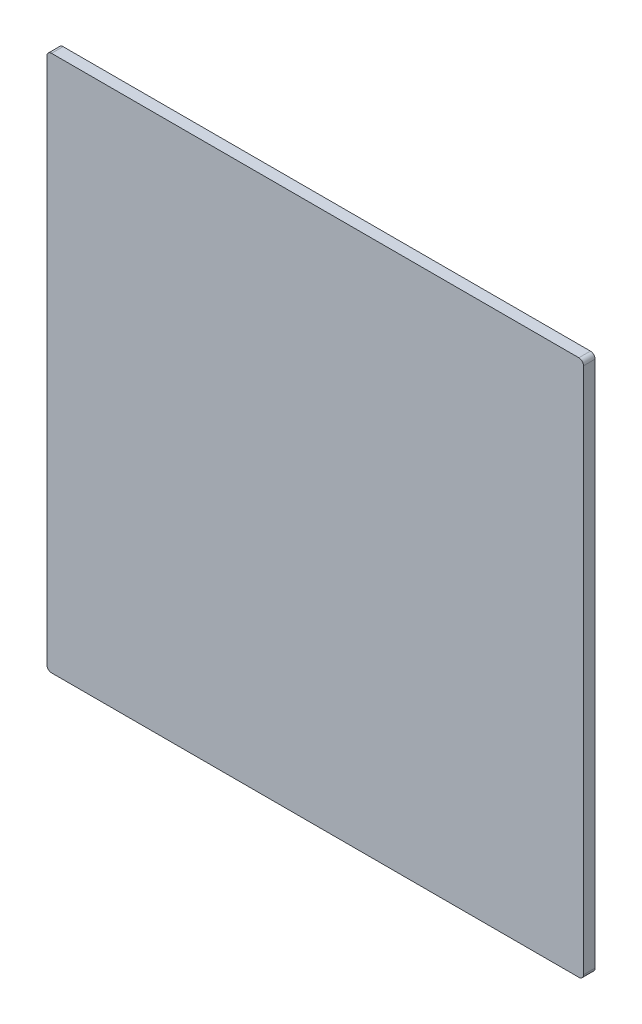
SolidWorks part; units mm, degrees
ref_plane "Front Plane" through (0, 0, 0) normal (0, 0, 1) x (1, 0, 0)
ref_plane "Top Plane" through (0, 0, 0) normal (0, 1, 0) x (1, 0, 0)
ref_plane "Right Plane" through (0, 0, 0) normal (1, 0, 0) x (0, 0, -1)
sketch "Sketch1" plane through (0, 0, 0) normal (0, 0, 1) x (1, 0, 0)
  line L0 (0, 0) -> (294.64, 0)
  line L1 (0, 0) -> (0, 294.64)
  line L2 (294.64, 0) -> (294.64, 294.64)
  line L3 (0, 294.64) -> (294.64, 294.64)
  dimension "D1" = 294.64
  dimension "D2" = 294.64
extrude "Boss-Extrude1" add sketch "Sketch1" along normal blind 6.35
fillet "Fillet1" radius 2.54 4 edges at (0, 0, 3.175) (294.64, 0, 3.175) (294.64, 294.64, 3.175) (0, 294.64, 3.175)
